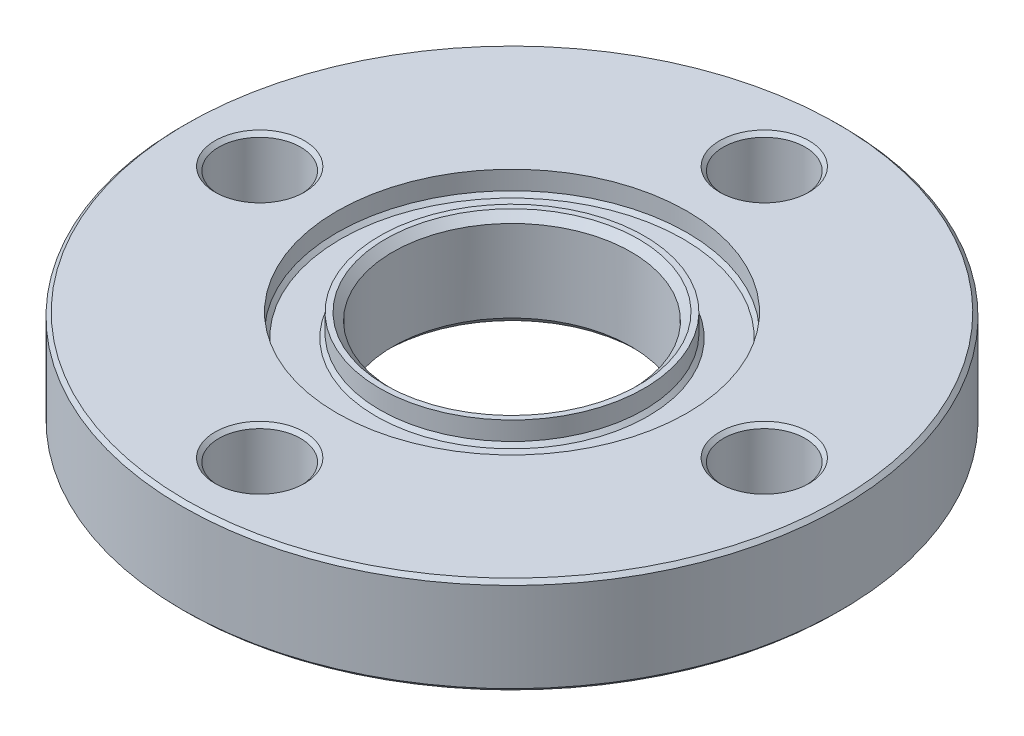
SolidWorks part; units mm, degrees
ref_plane "Alzado" through (0, 0, 0) normal (0, 0, 1) x (1, 0, 0)
ref_plane "Planta" through (0, 0, 0) normal (0, 1, 0) x (1, 0, 0)
ref_plane "Vista lateral" through (0, 0, 0) normal (1, 0, 0) x (0, 0, -1)
sketch "Croquis1" plane through (0, 0, 0) normal (1, 0, 0) x (0, 0, -1)
  line L0 (-16, -6.5) -> (-16, 6.5)
  line L1 (-16, 6.5) -> (-17.75, 6.5)
  line L2 (-17.75, 6.5) -> (-17.75, 3.5)
  line L3 (-17.75, 3.5) -> (-23.5, 3.5)
  line L4 (-23.5, 3.5) -> (-23.5, 6.5)
  line L5 (-23.5, 6.5) -> (-44.25, 6.5)
  line L6 (-44.25, 6.5) -> (-44.25, -6.5)
  line L7 (-44.25, -6.5) -> (-16, -6.5)
  line L8 (0, 0) -> (0, -50131.2274) construction
  point P10 (-16, 0)
  dimension "D1" = 16
  dimension "D2" = 23.5
  dimension "D3" = 17.75
  dimension "D4" = 44.25
  dimension "D5" = 3
  dimension "D6" = 13
revolve "Revolución1" add sketch "Croquis1" angle 360 about L8
sketch "Croquis2" plane through (0, 0, 0) normal (0, 1, 0) x (1, 0, 0)
  line L0 (0, 23.5) -> (0, 44.25) construction
  circle A0 centre (0, 33.875) radius 5.5
  circle A1 centre (33.875, 0) radius 5.5
  circle A2 centre (0, -33.875) radius 5.5
  circle A3 centre (-33.875, 0) radius 5.5
  circle A4 centre (0, 0) radius 23.5 construction
  circle A5 centre (0, 0) radius 23.5 construction
  circle A6 centre (0, 0) radius 44.25 construction
  point P10 (0, 0)
  point P19 (0, 33.875)
  dimension "D1" = 11
  dimension "D2" = 4
extrude "Cortar-Extruir1" cut sketch "Croquis2" against normal through all both and the other way through all
chamfer "Chaflán1" distance 1 angle 45 2 edges at (0, -6.5, 16) (0, 6.5, 16)
chamfer "Chaflán2" distance 0.5 angle 45 12 edges at (0, 3.5, 17.75) (0, 3.5, 23.5) (0, 6.5, 44.25) (0, -6.5, 44.25) (33.875, -6.5, 5.5) (33.875, 6.5, 5.5) (0, -6.5, -28.375) (0, 6.5, -28.375) (-33.875, -6.5, 5.5) (-33.875, 6.5, 5.5) (0, -6.5, 39.375) (0, 6.5, 39.375)
